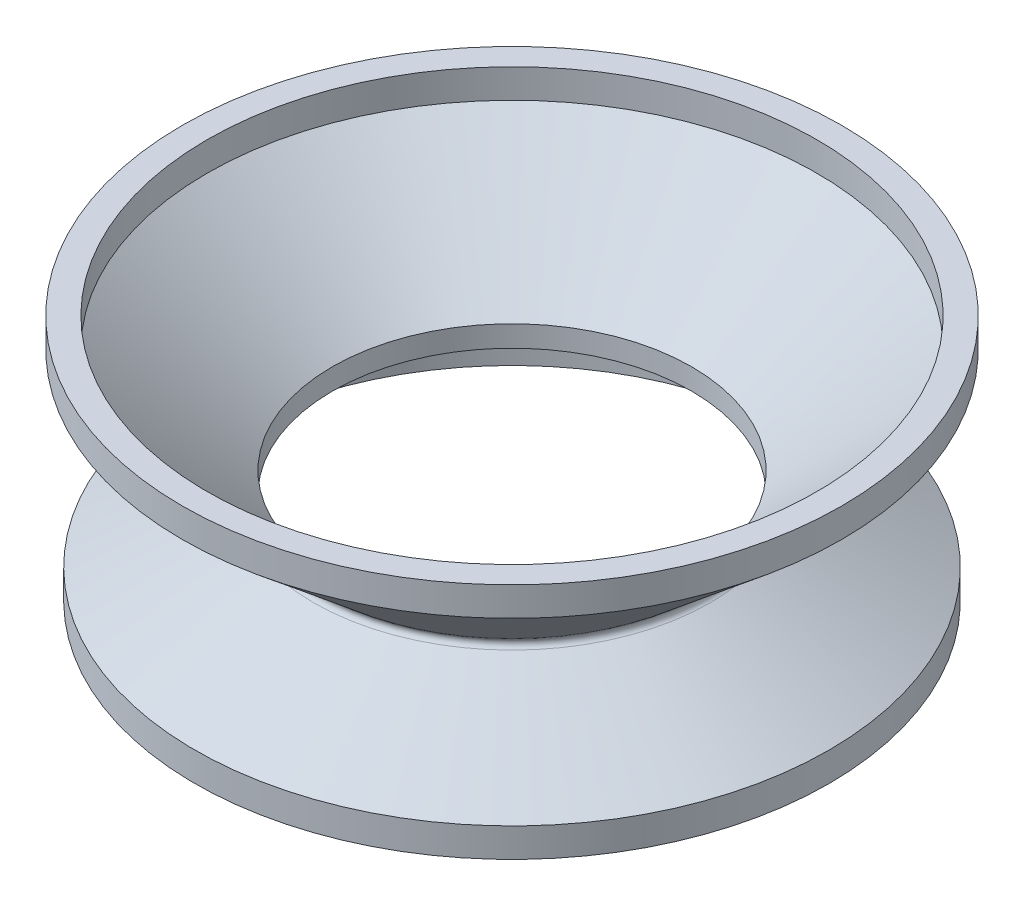
SolidWorks part; units mm, degrees
ref_plane "Front Plane" through (0, 0, 0) normal (0, 0, 1) x (1, 0, 0)
ref_plane "Top Plane" through (0, 0, 0) normal (0, 1, 0) x (1, 0, 0)
ref_plane "Right Plane" through (0, 0, 0) normal (1, 0, 0) x (0, 0, -1)
sketch "Sketch1" plane through (0, 0, 0) normal (0, 0, 1) x (1, 0, 0)
  line L0 (-42.6436, 0) -> (43.9692, 0) construction
  line L1 (0.6628, 0) -> (-8.8712, 8)
  line L2 (0.6628, 0) -> (-7.9975, -5)
  line L3 (1.4628, -0.6928) -> (-5.9975, -5)
  line L5 (-8.8712, 8) -> (-7.16, 8)
  line L6 (-7.9975, -5) -> (-5.9975, -5)
  line L7 (13.84, 7.609) -> (13.84, -7.609) construction
  line L8 (2.3996, -0.152) -> (-16.3835, 15.6089) construction
  line L9 (0.6628, 0) -> (-17.0263, 14.8429) construction
  line L10 (0.6628, 0) -> (-17.9865, -10.7671) construction
  line L11 (2.3996, -0.152) -> (-17.4865, -11.6332) construction
  line L12 (0.6628, 0) -> (2.2628, 0) construction
  line L13 (1.4628, -0.6928) -> (1.4628, 0.7647)
  line L14 (1.4628, 0.7647) -> (-7.16, 8)
  point P11 (1.4628, 0)
  dimension "D1" = 40
  dimension "D2" = 30
  dimension "D4" = 8
  dimension "D5" = 5
  dimension "D6" = 21
  dimension "D7" = 1.6
  dimension "D8" = 1.1
  dimension "D3" = 1
revolve "Revolve1" add sketch "Sketch1" angle 360 about L7
scale "Scale1" [suppressed]
fillet "Fillet2" radius 0.4 1 edges at (0.6628, 0, 0)
sketch "Sketch2" plane through (0, 8, 0) normal (0, 1, 0) x (1, 0, 0)
  circle A0 centre (13.84, 0) radius 22.7113 construction
  circle A1 centre (13.84, 0) radius 21 construction
  circle A2 centre (13.84, 0) radius 22.7113
  circle A3 centre (13.84, 0) radius 21
extrude "Boss-Extrude1" add sketch "Sketch2" along normal blind 2
sketch "Sketch3" plane through (0, -5, 0) normal (0, -1, 0) x (1, 0, 0)
  circle A0 centre (13.84, 0) radius 19.8375 construction
  circle A1 centre (13.84, 0) radius 21.8375 construction
  circle A2 centre (13.84, 0) radius 19.8375
  circle A3 centre (13.84, 0) radius 21.8375
extrude "Boss-Extrude2" add sketch "Sketch3" along normal blind 2
